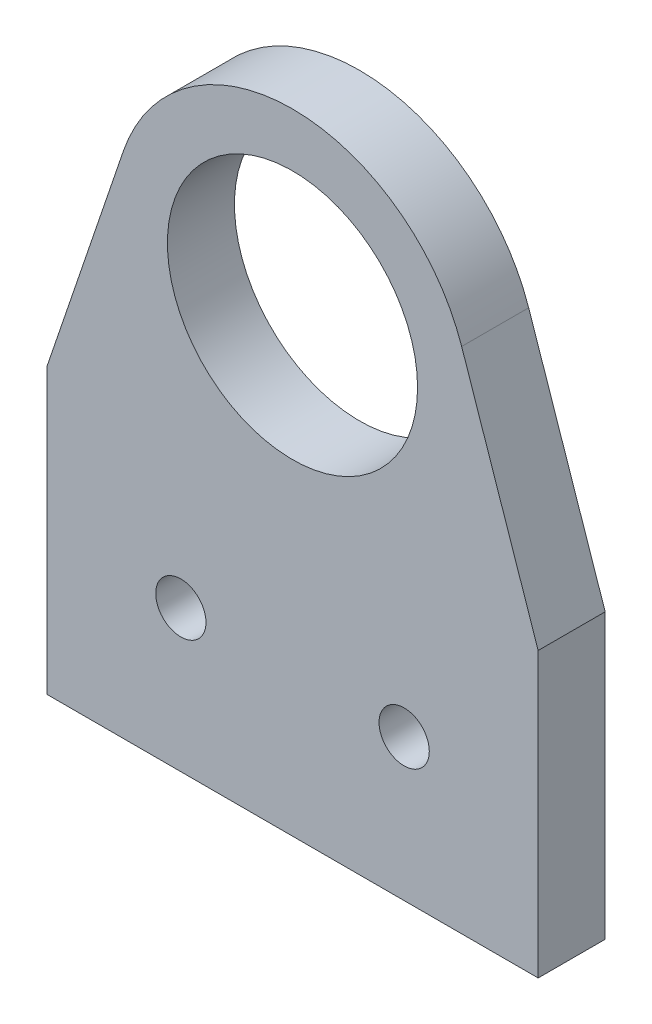
SolidWorks part; units mm, degrees
ref_plane "Front Plane" through (0, 0, 0) normal (0, 0, 1) x (1, 0, 0)
ref_plane "Top Plane" through (0, 0, 0) normal (0, 1, 0) x (1, 0, 0)
ref_plane "Right Plane" through (0, 0, 0) normal (1, 0, 0) x (0, 0, -1)
sketch "Sketch1" plane through (0, 0, 0) normal (0, 0, 1) x (1, 0, 0)
  line L0 (-22, -15) -> (-15.1483, 5.1508)
  line L1 (15.1483, 5.1508) -> (22, -15)
  line L6 (-22, -40.4) -> (22, -40.4)
  line L7 (-22, -40.4) -> (-22, -15)
  line L8 (-22, -15) -> (22, -15)
  line L9 (22, -40.4) -> (22, -15)
  line L10 (-22, -40.4) -> (22, -15) construction
  line L11 (-22, -15) -> (22, -40.4) construction
  circle A1 centre (0, 0) radius 11.2
  arc A3 (-15.1483, 5.1508) -> (15.1483, 5.1508) centre (0, 0) cw
  point P10 (0, -27.7)
  dimension "D1" = 25.4
  dimension "D2" = 22.4
  dimension "D5" = 16
  dimension "D3" = 15
  dimension "D4" = 44
extrude "Boss-Extrude1" add sketch "Sketch1" along normal blind 6 contours A3 L0 L8 L1 A1 | L6 L9 L8 L7
sketch "Sketch2" plane through (0, 0, 6) normal (0, 0, 1) x (1, 0, 0)
  line L0 (-22, -40.4) -> (-22, -15) construction
  point P0 (-10, -27.7)
  point P1 (10, -27.7)
  point P5 (-22, -27.7)
  dimension "D1" = 10
  dimension "D2" = 10
hole_wizard "M4 Clearance Hole1" positions "Sketch3" profile "Sketch4" hole size "M4" standard "ANSI Metric" end condition through all
sketch "Sketch3" plane through (0, 0, 6) normal (0, 0, 1) x (1, 0, 0)
  point P0 (-10, -27.7)
  point P3 (10, -27.7)
sketch "Sketch4" plane through (-10, -27.7, 6) normal (1, 0, 0) x (0, -1, 0)
  line L0 (0, 0) -> (0, 6)
  line L1 (0, 6) -> (2.25, 6)
  line L2 (2.25, 6) -> (2.25, 0)
  line L5 (2.25, 0) -> (0, 0)
  line L11 (0, -6.35) -> (0, 107.95) construction
  dimension "Thru Hole Dia." = 4.5
  dimension "Thru Hole Depth" = 6
